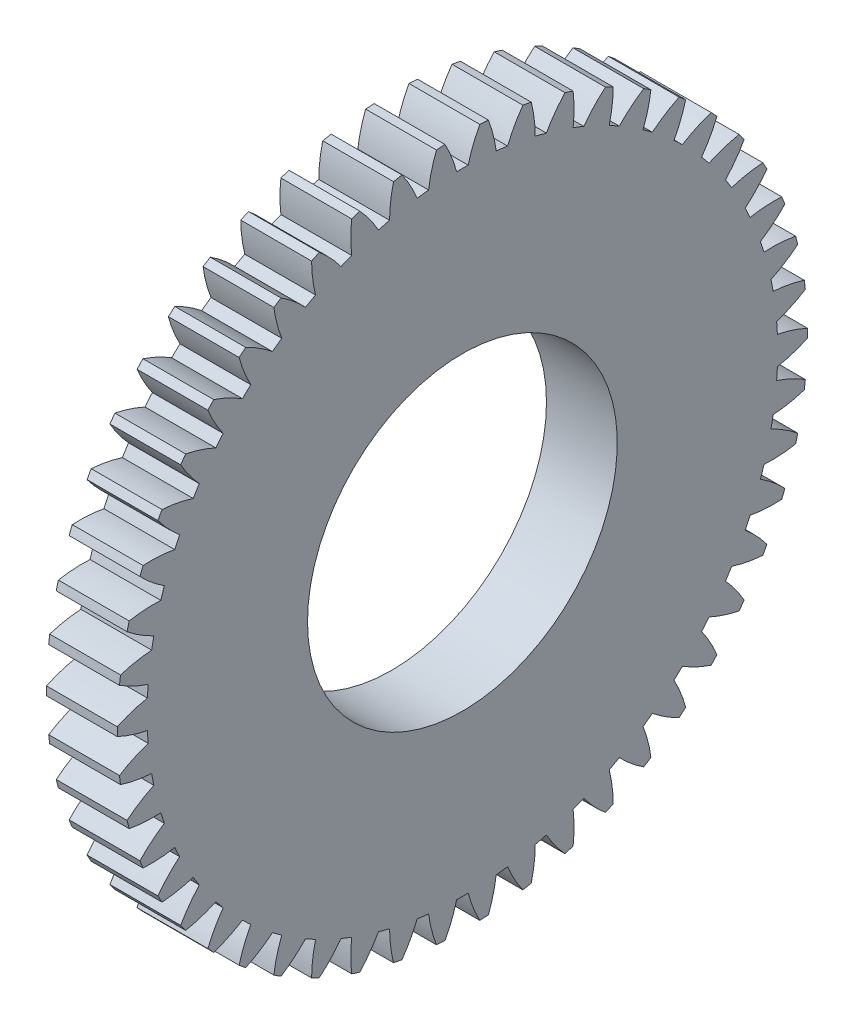
SolidWorks part; units mm, degrees
ref_plane "Plane1" through (0, 0, 0) normal (0, 0, 1) x (1, 0, 0)
ref_plane "Plane2" through (0, 0, 0) normal (0, 1, 0) x (1, 0, 0)
ref_plane "Plane3" through (0, 0, 0) normal (1, 0, 0) x (0, 0, -1)
sketch "HoldingSke" plane through (0, 0, 0) normal (0, 1, 0) x (1, 0, 0)
  line L0 (0, 0) -> (0.4285, -0.5107)
  line L1 (-15, 0) -> (100, 0) construction
  line L2 (0, 0) -> (-2.1039, 2.3779)
  line L3 (0, 0) -> (-11.863, 4.5341)
  line L4 (0, 0) -> (5.5511, 6.6156)
  line L5 (0, 0) -> (-46.8476, -17.4728)
  line L6 (0, 0) -> (-6.6317, -4.4744)
  line L7 (-2.1039, 2.3779) -> (8.6586, 51.2059)
  line L8 (-76.2, 54.61) -> (-72.9, 54.61)
  line L9 (-71.009, 38.7566) -> (-53.1078, 45.2721)
  line L10 (-76.2, 71.12) -> (104.1128, 71.12)
  line L11 (0, 0) -> (-8, 0)
  line L12 (-76.2, 101.6) -> (-76.147, 101.6)
  line L13 (24.9733, 27.94) -> (52.9518, 28.4284)
  line L14 (24.9733, 27.94) -> (24.9743, 27.94)
  line L15 (24.9733, 27.94) -> (100.4006, 29.5858)
  line L16 (-63.627, -1.5) -> (-12.827, -1.5)
  circle A0 centre (0, 0) radius 17.5
  circle A1 centre (0, 0) radius 35.624
  circle A2 centre (0, 0) radius 37.5
  circle A3 centre (0, 0) radius 17.5
  dimension "MHD" = 71.248
  dimension "Hub_dia" = 75
  dimension "Bore" = 35
  dimension "MBD" = 35
  dimension "Num_teeth" = 50
  dimension "Pitch" = 0.6667
  dimension "Overall_len" = 50
  dimension "Show_teeth" = 50
  dimension "Thickness" = 8
  dimension "OAL" = 50.0001
  dimension "T_dim" = 3.3
  dimension "Ap" = 20
  dimension "H" = 19.05
  dimension "Pitch_radius" = 180.3128
  dimension "Width" = 8
  dimension "Backlash" = 0.053
  dimension "Addendum_fac" = 1
  dimension "Dedendum_fac" = 1.25
  dimension "Clearance_fac" = 0.25
  dimension "Dedendum_add" = 0.001
  dimension "Module" = 1.5
sketch "BasProSke" plane through (0, 0, 0) normal (0, 1, 0) x (1, 0, 0)
  line L0 (-10, 0) -> (60, 0) construction
  line L1 (0, 0) -> (0, 39)
  line L2 (0, 0) -> (8, 0)
  line L3 (8, 0) -> (8, 39)
  line L4 (8, 39) -> (0, 39)
  dimension "Thickness" = 8
  dimension "Diameter" = 78
revolve "Base-Revolve" add sketch "BasProSke" angle 360 about L0
sketch "TooCutSke" plane through (0, 0, 0) normal (1, 0, 0) x (0, 0, -1)
  line L1 (0, 0) -> (0, 107) construction
  line L2 (0, 0) -> (-1.2706, 37.4785) construction
  line L3 (0, 0) -> (-4.7073, 74.8207) construction
  line L4 (-1.2706, 37.4785) -> (-2.3537, 37.4103) construction
  arc A0 (0.65, 35.6181) -> (-0.65, 35.6181) centre (0, 0) ccw
  arc A1 (1.9801, 38.9751) -> (-1.9801, 38.9751) centre (0, 0) ccw
  circle A2 centre (0, 0) radius 37.5 construction
  circle A3 centre (0, 0) radius 35.2385 construction
  arc A4 (-0.65, 35.6181) -> (-1.9801, 38.9751) centre (-15.1589, 31.8113) ccw
  arc A5 (1.9801, 38.9751) -> (0.65, 35.6181) centre (15.1589, 31.8113) ccw
  dimension "Root_dia" = 71.248
  dimension "Overcut_dia" = 78.0508
  dimension "Pitch_dia" = 75
  dimension "Base_dia" = 70.4769
  dimension "Flank_rad" = 15
  dimension "Half_ang" = 3.6
  dimension "Half_CT" = 1.0852
extrude "ToothCut" cut sketch "TooCutSke" along normal through all
fillet "Breaks" [suppressed] radius 0.03
fillet "RootFillets" [suppressed] radius 0.376
pattern_circular "TeethCuts" count 50 every 7.2 about axis through (-10, 0, 0) along (1, 0, 0) of "ToothCut", "RootFillets", "Breaks"
sketch "HubNeaOneSke" plane through (0, 0, 0) normal (-1, 0, 0) x (0, 0, 1)
  circle A0 centre (0, 0) radius 35.624
  dimension "Diameter" = 71.248
extrude "HubNearOne" [suppressed] add sketch "HubNeaOneSke" along normal blind 42.0001
sketch "HubNeaBotSke" plane through (0, 0, 0) normal (-1, 0, 0) x (0, 0, 1)
  circle A0 centre (0, 0) radius 35.624
  dimension "Diameter" = 71.248
extrude "HubNearBoth" [suppressed] add sketch "HubNeaBotSke" along normal blind 21
ref_plane "FarPln" through (8, 0, 0) normal (1, 0, 0) x (0, 0, -1)
sketch "HubFarSke" plane through (8, 0, 0) normal (1, 0, 0) x (0, 0, -1)
  circle A0 centre (0, 0) radius 35.624
  dimension "Diameter" = 71.248
extrude "HubFar" [suppressed] add sketch "HubFarSke" along normal blind 21
sketch "BorSke" plane through (0, 0, 0) normal (1, 0, 0) x (0, 0, -1)
  circle A0 centre (0, 0) radius 17.5
  dimension "Diameter" = 35
extrude "Bore" cut sketch "BorSke" along normal mid plane 100.0001
sketch "KeySke" plane through (0, 0, 0) normal (1, 0, 0) x (0, 0, -1)
  line L0 (-5, 0) -> (-5, 20.8)
  line L1 (-5, 20.8) -> (5, 20.8)
  line L2 (5, 20.8) -> (5, 0)
  line L3 (0, 0) -> (0, 34) construction
  line L4 (-5, 0) -> (5, 0)
  dimension "Offset" = 20.8
  dimension "Width" = 10
extrude "Keyway" [suppressed] cut sketch "KeySke" along normal mid plane 100.0001
pattern_circular "Keyway2" [suppressed] count 2 every 90 about axis through (-10, 0, 0) along (1, 0, 0)
equation "' \"Module@HoldingSke\" = 6.35"
equation "' \"Num_teeth@HoldingSke\" = 12"
equation "' \"Ap@HoldingSke\" =  20"
equation "' \"Ap@HoldingSke\" = 20"
equation "' \"Width@HoldingSke\" = 0.5 * 25.4"
equation "' \"Hub_dia@HoldingSke\"= 1 * 25.4"
equation "' \"Hub_dia@HoldingSke\" = 1 * 25.4"
equation "' \"Overall_len@HoldingSke\" = 1.0 * 25.4"
equation "' \"Bore@HoldingSke\" = 0.75 * 25.4"
equation "' \"T_dim@HoldingSke\" = 0.1 * 25.4"
equation "' \"Width@KeySke\" = 0.25 * 25.4"
equation "' \"Show_teeth@HoldingSke\" = 13"
equation "' \"Backlash@HoldingSke\" = 0.009 * 25.4"
equation "' \"Addendum_fac@HoldingSke\" = 1.0"
equation "' \"Dedendum_fac@HoldingSke\" = 1.25"
equation "' \"Dedendum_add@HoldingSke\" = 0.00005 * 25.4"
equation "' \"Clearance_fac@HoldingSke\" = 0.25"
equation "\"Pitch@HoldingSke\" = 1 / \"Module@HoldingSke\""
equation "\"Overcut_dia@TooCutSke\" = (\"Num_teeth@HoldingSke\" + 2 * \"Addendum_fac@HoldingSke\") / \"Pitch@HoldingSke\" + 0.002 * 25.4"
equation "\"Pitch_dia@TooCutSke\" = \"Num_teeth@HoldingSke\" / \"Pitch@HoldingSke\""
equation "\"Base_dia@TooCutSke\" = \"Num_teeth@HoldingSke\" / \"Pitch@HoldingSke\" * cos((\"Ap@HoldingSke\"  * 3.14159265 / 180))"
equation "\"Root_dia@TooCutSke\" = (\"Num_teeth@HoldingSke\" + 2) / \"Pitch@HoldingSke\" - 2 * (\"Addendum_fac@HoldingSke\" + \"Dedendum_fac@HoldingSke\") / \"Pitch@HoldingSke\" - \"Dedendum_add@HoldingSke\" * 2"
equation "\"Half_ang@TooCutSke\" = 180 / \"Num_teeth@HoldingSke\""
equation "\"Half_CT@TooCutSke\" = \"Num_teeth@HoldingSke\" / \"Pitch@HoldingSke\" * sin((3.14159265 / 2 / \"Num_teeth@HoldingSke\")) / 2 - 7 * \"Backlash@HoldingSke\" / 4"
equation "\"Flank_rad@TooCutSke\" = \"Num_teeth@HoldingSke\" / \"Pitch@HoldingSke\" / 5"
equation "\"Radius@RootFillets\" = \"Clearance_fac@HoldingSke\" / \"Pitch@HoldingSke\" + \"Dedendum_add@HoldingSke\""
equation "\"Break_rad@Breaks\" = 0.02 / \"Pitch@HoldingSke\""
equation "\"Thickness@HoldingSke\" = \"Width@HoldingSke\""
equation "\"OAL@HoldingSke\" = \"Thickness@HoldingSke\""
equation "\"MHD@HoldingSke\" = (\"Num_teeth@HoldingSke\" + 2) / \"Pitch@HoldingSke\" - 2 * (\"Addendum_fac@HoldingSke\" + \"Dedendum_fac@HoldingSke\")  / \"Pitch@HoldingSke\" - \"Dedendum_add@HoldingSke\" * 2"
equation "\"MBD@HoldingSke\" = (\"Num_teeth@HoldingSke\" + 2) / \"Pitch@HoldingSke\" - 2 * (\"Addendum_fac@HoldingSke\" + \"Dedendum_fac@HoldingSke\")  / \"Pitch@HoldingSke\" - \"Dedendum_add@HoldingSke\" * 2 - 0.002 * 25.4"
equation "\"MHD@HoldingSke\" = ((sgn( \"MHD@HoldingSke\" - \"Hub_dia@HoldingSke\" )-1)*( \"MHD@HoldingSke\" - \"Hub_dia@HoldingSke\" ))/-2+ \"Hub_dia@HoldingSke\""
equation "\"MBD@HoldingSke\" = ((sgn( \"MBD@HoldingSke\" - \"Bore@HoldingSke\" )-1)*( \"MBD@HoldingSke\" - \"Bore@HoldingSke\" ))/-2+ \"Bore@HoldingSke\""
equation "\"OAL@HoldingSke\" = ((sgn( \"OAL@HoldingSke\" - \"Overall_len@HoldingSke\" )+1)*( \"OAL@HoldingSke\" - \"Overall_len@HoldingSke\" ))/2 + \"Overall_len@HoldingSke\" + 0.000002 * 25.4"
equation "\"Num_teeth@TeethCuts\" = int( \"Show_teeth@HoldingSke\" ) + 1"
equation "\"Num_teeth@TeethCuts\" = ((sgn( \"Num_teeth@TeethCuts\" - \"Num_teeth@HoldingSke\" )-1)*( \"Num_teeth@TeethCuts\" - \"Num_teeth@HoldingSke\" ))/-2+ \"Num_teeth@HoldingSke\""
equation "\"Num_teeth@TeethCuts\" = ((sgn( \"Num_teeth@TeethCuts\" - 2.0)+1)*( \"Num_teeth@TeethCuts\" - 2.0))/2 +2.0"
equation "\"Angle@TeethCuts\" = 360.0 / \"Num_teeth@HoldingSke\""
equation "\"Diameter@BasProSke\" = (\"Num_teeth@HoldingSke\" + 2 * \"Addendum_fac@HoldingSke\") / \"Pitch@HoldingSke\""
equation "\"Thickness@BasProSke\"  = \"Thickness@HoldingSke\""
equation "' \"Fillet_rad@BasProSke\" =  \"Thickness@HoldingSke\" * 0.05"
equation "' \"Fillet_rad@BasProSke\" = \"Thickness@HoldingSke\" * 0.05"
equation "\"MHD@HoldingSke\" = ((sgn( \"MHD@HoldingSke\" - \"Root_dia@TooCutSke\" )-1)*( \"MHD@HoldingSke\" - \"Root_dia@TooCutSke\" ))/-2+ \"Root_dia@TooCutSke\""
equation "\"Diameter@HubNeaOneSke\" = \"MHD@HoldingSke\""
equation "\"Length@HubNearOne\" = \"OAL@HoldingSke\" - \"Thickness@BasProSke\""
equation "\"Diameter@HubNeaBotSke\" = \"MHD@HoldingSke\""
equation "\"Length@HubNearBoth\" = ( \"OAL@HoldingSke\" - \"Thickness@BasProSke\" ) / 2.0"
equation "\"Thickness@FarPln\" = \"Thickness@BasProSke\""
equation "\"Diameter@HubFarSke\" = \"MHD@HoldingSke\""
equation "\"Length@HubFar\" = ( \"OAL@HoldingSke\" - \"Thickness@BasProSke\" ) / 2.0"
equation "\"Diameter@BorSke\" = \"MBD@HoldingSke\""
equation "\"D1@Bore\" = \"OAL@HoldingSke\" * 2.0"
equation "\"D1@Keyway\" = \"OAL@HoldingSke\" * 2.0"
equation "\"Offset@KeySke\" = \"T_dim@HoldingSke\" + \"MBD@HoldingSke\" / 2.0"
